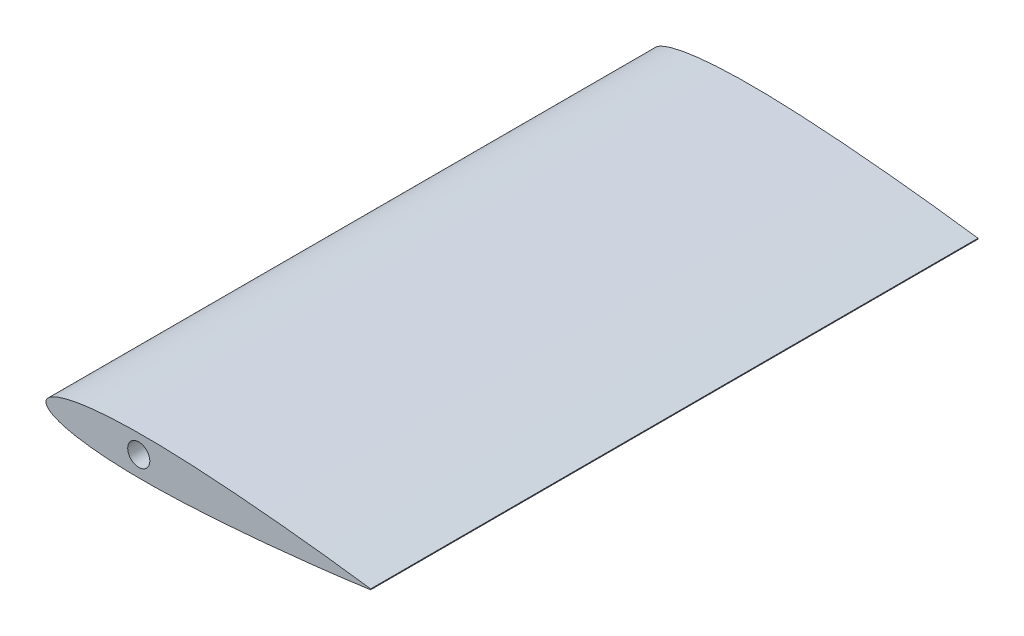
SolidWorks part; units mm, degrees
ref_plane "Front Plane" through (0, 0, 0) normal (0, 0, 1) x (1, 0, 0)
ref_plane "Top Plane" through (0, 0, 0) normal (0, 1, 0) x (1, 0, 0)
ref_plane "Right Plane" through (0, 0, 0) normal (1, 0, 0) x (0, 0, -1)
curve "Curve1"
  spline degree 3 poles (1, 0.0013, 0) (0.9998, 0.0013, 0) (0.999, 0.0014, 0) (0.9973, 0.0016, 0) (0.9944, 0.002, 0) (0.9903, 0.0026, 0) (0.9851, 0.0033, 0) (0.9788, 0.0042, 0) (0.9713, 0.0052, 0) (0.9627, 0.0064, 0) (0.9531, 0.0077, 0) (0.9424, 0.0091, 0) (0.9307, 0.0106, 0) (0.9179, 0.0122, 0) (0.9042, 0.014, 0) (0.8895, 0.0158, 0) (0.874, 0.0177, 0) (0.8575, 0.0196, 0) (0.8402, 0.0217, 0) (0.8222, 0.0237, 0) (0.8033, 0.0259, 0) (0.7838, 0.028, 0) (0.7636, 0.0302, 0) (0.7428, 0.0324, 0) (0.7214, 0.0345, 0) (0.6995, 0.0367, 0) (0.6772, 0.0388, 0) (0.6544, 0.0409, 0) (0.6313, 0.043, 0) (0.6078, 0.045, 0) (0.5841, 0.0469, 0) (0.5602, 0.0488, 0) (0.5362, 0.0505, 0) (0.5121, 0.0522, 0) (0.4879, 0.0537, 0) (0.4638, 0.0551, 0) (0.4398, 0.0563, 0) (0.4159, 0.0574, 0) (0.3922, 0.0583, 0) (0.3688, 0.0591, 0) (0.3456, 0.0596, 0) (0.3228, 0.0599, 0) (0.3005, 0.0601, 0) (0.2786, 0.06, 0) (0.2572, 0.0596, 0) (0.2364, 0.0591, 0) (0.2162, 0.0583, 0) (0.1966, 0.0572, 0) (0.1778, 0.056, 0) (0.1597, 0.0544, 0) (0.1425, 0.0527, 0) (0.126, 0.0507, 0) (0.1104, 0.0486, 0) (0.0958, 0.0462, 0) (0.0821, 0.0436, 0) (0.0693, 0.0408, 0) (0.0576, 0.0378, 0) (0.0468, 0.0347, 0) (0.0372, 0.0313, 0) (0.0286, 0.0279, 0) (0.0211, 0.0243, 0) (0.0147, 0.0206, 0) (0.0094, 0.0167, 0) (0.0053, 0.0128, 0) (0.0023, 0.0087, 0) (0.0004, 0.0044, 0) (-0.0002, 0, 0) (0.0004, -0.0044, 0) (0.0023, -0.0087, 0) (0.0053, -0.0128, 0) (0.0094, -0.0167, 0) (0.0147, -0.0206, 0) (0.0211, -0.0243, 0) (0.0286, -0.0279, 0) (0.0372, -0.0313, 0) (0.0468, -0.0347, 0) (0.0576, -0.0378, 0) (0.0693, -0.0408, 0) (0.0821, -0.0436, 0) (0.0958, -0.0462, 0) (0.1104, -0.0486, 0) (0.126, -0.0507, 0) (0.1425, -0.0527, 0) (0.1597, -0.0544, 0) (0.1778, -0.056, 0) (0.1966, -0.0572, 0) (0.2162, -0.0583, 0) (0.2364, -0.0591, 0) (0.2572, -0.0596, 0) (0.2786, -0.06, 0) (0.3005, -0.0601, 0) (0.3228, -0.0599, 0) (0.3456, -0.0596, 0) (0.3688, -0.0591, 0) (0.3922, -0.0583, 0) (0.4159, -0.0574, 0) (0.4398, -0.0563, 0) (0.4638, -0.0551, 0) (0.4879, -0.0537, 0) (0.5121, -0.0522, 0) (0.5362, -0.0505, 0) (0.5602, -0.0488, 0) (0.5841, -0.0469, 0) (0.6078, -0.045, 0) (0.6313, -0.043, 0) (0.6544, -0.0409, 0) (0.6772, -0.0388, 0) (0.6995, -0.0367, 0) (0.7214, -0.0345, 0) (0.7428, -0.0324, 0) (0.7636, -0.0302, 0) (0.7838, -0.028, 0) (0.8033, -0.0259, 0) (0.8222, -0.0237, 0) (0.8402, -0.0217, 0) (0.8575, -0.0196, 0) (0.874, -0.0177, 0) (0.8895, -0.0158, 0) (0.9042, -0.014, 0) (0.9179, -0.0122, 0) (0.9307, -0.0106, 0) (0.9424, -0.0091, 0) (0.9531, -0.0077, 0) (0.9627, -0.0064, 0) (0.9713, -0.0052, 0) (0.9788, -0.0042, 0) (0.9851, -0.0033, 0) (0.9903, -0.0026, 0) (0.9944, -0.002, 0) (0.9973, -0.0016, 0) (0.999, -0.0014, 0) (0.9998, -0.0013, 0) (1, -0.0013, 0) knots 0 0 0 0 0.000289 0.001156 0.002598 0.004612 0.007194 0.010336 0.014031 0.018272 0.023046 0.028343 0.03415 0.040454 0.047238 0.054489 0.062187 0.070314 0.078852 0.08778 0.097078 0.106722 0.116691 0.126961 0.137507 0.148306 0.159331 0.170556 0.181957 0.193504 0.205171 0.216932 0.228758 0.240621 0.252495 0.26435 0.276161 0.287898 0.299536 0.311047 0.322405 0.333584 0.344559 0.355306 0.3658 0.376018 0.385937 0.395538 0.404798 0.413699 0.422221 0.430349 0.438066 0.445357 0.452209 0.458612 0.464554 0.47003 0.475035 0.479569 0.483637 0.48725 0.490431 0.493219 0.495674 0.497891 0.5 0.502109 0.504326 0.506781 0.509569 0.51275 0.516363 0.520431 0.524965 0.52997 0.535446 0.541388 0.547791 0.554643 0.561934 0.569651 0.577779 0.586301 0.595202 0.604462 0.614063 0.623982 0.6342 0.644694 0.655441 0.666416 0.677595 0.688953 0.700464 0.712102 0.723839 0.73565 0.747505 0.759379 0.771242 0.783068 0.794829 0.806496 0.818043 0.829444 0.840669 0.851694 0.862493 0.873039 0.883309 0.893278 0.902922 0.91222 0.921148 0.929686 0.937813 0.945511 0.952762 0.959546 0.96585 0.971657 0.976954 0.981728 0.985969 0.989664 0.992806 0.995388 0.997402 0.998844 0.999711 1 1 1 1
sketch "Sketch7" plane through (0, 0, 0) normal (0, 0, 1) x (1, 0, 0)
  line L0 (1, -0.1046) -> (1, -0.0305)
  spline S1 degree 3 poles (1, -0.0305) (0.4391, 0.0483) (-1.6744, 0.334) (-4.6175, 0.6842) (-8.1327, 1.0467) (-10.798, 1.2847) (-13.3462, 1.4715) (-15.4585, 1.5943) (-17.5341, 1.6757) (-19.5296, 1.7066) (-21.2181, 1.6828) (-22.5985, 1.6201) (-23.6814, 1.5397) (-24.6714, 1.4322) (-25.4327, 1.3183) (-25.9877, 1.2132) (-26.3625, 1.1311) (-26.7078, 1.0436) (-27.0228, 0.9512) (-27.3068, 0.8541) (-27.5593, 0.7526) (-27.7796, 0.6472) (-27.9675, 0.5378) (-28.1226, 0.4249) (-28.2448, 0.3081) (-28.3336, 0.1871) (-28.3879, 0.0614) (-28.4059, -0.0675) (-28.3879, -0.1965) (-28.3336, -0.3222) (-28.2448, -0.4432) (-28.1226, -0.5599) (-27.9675, -0.6729) (-27.7796, -0.7822) (-27.5593, -0.8877) (-27.3068, -0.9892) (-27.0228, -1.0863) (-26.7078, -1.1787) (-26.3625, -1.2662) (-25.8453, -1.3794) (-25.1286, -1.5039) (-24.1886, -1.6243) (-22.9535, -1.7363) (-21.4032, -1.8152) (-19.2995, -1.8449) (-17.0681, -1.7988) (-14.7563, -1.6926) (-12.6416, -1.5581) (-10.3295, -1.3786) (-8.3035, -1.1944) (-5.6924, -0.9326) (-3.1098, -0.6438) (-0.6443, -0.3306) (0.587, -0.1624) (0.9486, -0.1118) (1, -0.1046) knots 0 0 0 0 0.028343 0.106722 0.148306 0.205171 0.240621 0.276161 0.311047 0.344559 0.376018 0.395538 0.413699 0.430349 0.445357 0.452209 0.458612 0.464554 0.47003 0.475035 0.479569 0.483637 0.48725 0.490431 0.493219 0.495674 0.497891 0.5 0.502109 0.504326 0.506781 0.509569 0.51275 0.516363 0.520431 0.524965 0.52997 0.535446 0.541388 0.547791 0.561934 0.577779 0.595202 0.623982 0.655441 0.700464 0.73565 0.771242 0.806496 0.851694 0.873039 0.937813 0.981728 0.997402 1 1 1 1
extrude "Boss-Extrude4" add sketch "Sketch7" along normal blind 55
sketch "Sketch8" plane through (0, 0, 55) normal (0, 0, 1) x (1, 0, 0)
  line L0 (1, -0.1046) -> (1, -0.0305) construction
  circle A0 centre (-20, 0) radius 1
  dimension "D1" = 21
extrude "Cut-Extrude3" cut sketch "Sketch8" against normal through all
